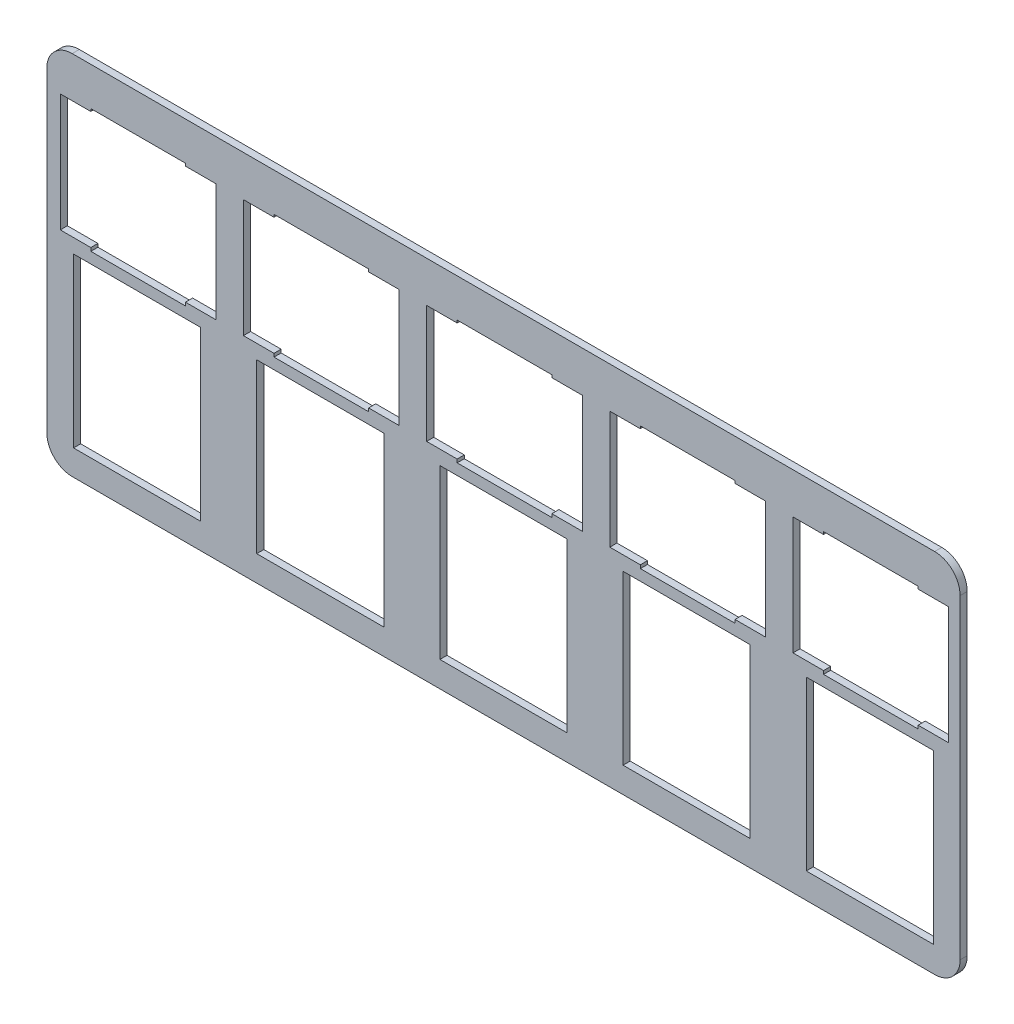
SolidWorks part; units mm, degrees
ref_plane "Ebene vorne" through (0, 0, 0) normal (0, 0, 1) x (1, 0, 0)
ref_plane "Ebene oben" through (0, 0, 0) normal (0, 1, 0) x (1, 0, 0)
ref_plane "Ebene rechts" through (0, 0, 0) normal (1, 0, 0) x (0, 0, -1)
sketch "Skizze1" plane through (0, 0, 0) normal (0, 0, 1) x (1, 0, 0)
  line L1 (-89.75, -36) -> (89.75, -36)
  line L2 (-89.75, -36) -> (-89.75, 36)
  line L3 (-89.75, 36) -> (89.75, 36)
  line L4 (89.75, -36) -> (89.75, 36)
  line L5 (-89.75, -36) -> (89.75, 36) construction
  line L6 (-89.75, 36) -> (89.75, -36) construction
  point P0 (0, 0)
  dimension "D1" = 179.5
  dimension "D2" = 72
extrude "Aufsatz-Linear austragen1" add sketch "Skizze1" along normal blind 1.4
fillet "Verrundung1" radius 5 4 edges at (-89.75, 36, 0.7) (-89.75, -36, 0.7) (89.75, -36, 0.7) (89.75, 36, 0.7)
sketch "Skizze2" plane through (0, 0, 1.4) normal (0, 0, 1) x (1, 0, 0)
  line L0 (63.205, 4.818) -> (81.205, 4.818) construction
  line L1 (59.5127, 27.0001) -> (59.5127, -27.0001) construction
  line L2 (84.4873, -27.0001) -> (84.4873, 27.0001) construction
  line L3 (80.5, 30.9874) -> (63.5, 30.9874) construction
  line L4 (63.205, 4.818) -> (81.205, 4.818) construction
  line L5 (59.5127, 27.0001) -> (59.5127, -27.0001) construction
  line L6 (84.4873, -27.0001) -> (84.4873, 27.0001) construction
  line L7 (80.5, 30.9874) -> (63.5, 30.9874) construction
  line L8 (81.205, 27.818) -> (63.205, 27.818) construction
  line L9 (81.205, 27.818) -> (63.205, 27.818) construction
  line L10 (63.5, -30.9874) -> (80.5, -30.9874) construction
  line L11 (63.5, -30.9874) -> (80.5, -30.9874) construction
  line L13 (84.4873, -30.9874) -> (59.5127, -30.9874)
  line L14 (84.4873, -30.9874) -> (84.4873, 2.0126)
  line L15 (84.4873, 2.0126) -> (59.5127, 2.0126)
  line L16 (59.5127, -30.9874) -> (59.5127, 2.0126)
  dimension "D1" = 33
extrude "Schnitt-Linear austragen1" cut sketch "Skizze2" against normal through all
sketch "Skizze3" plane through (0, 0, 1.4) normal (0, 0, 1) x (1, 0, 0)
  line L0 (63.205, 4.818) -> (81.205, 4.818) construction
  line L1 (62.905, 28.468) -> (81.505, 28.468)
  line L2 (62.905, 28.468) -> (62.905, 27.968)
  line L3 (62.905, 4.168) -> (81.505, 4.168)
  line L4 (81.505, 28.468) -> (81.505, 27.968)
  line L5 (81.205, 27.818) -> (63.205, 27.818) construction
  line L6 (81.205, 26.848) -> (81.205, 27.818) construction
  line L7 (62.905, 4.818) -> (62.905, 4.168)
  line L8 (62.905, 27.968) -> (56.905, 27.968)
  line L10 (62.905, 4.818) -> (56.905, 4.818)
  line L11 (56.905, 27.968) -> (56.905, 4.818)
  line L12 (81.505, 27.968) -> (87.505, 27.968)
  line L14 (81.505, 4.818) -> (87.505, 4.818)
  line L15 (87.505, 27.968) -> (87.505, 4.818)
  line L16 (81.505, 4.818) -> (81.505, 4.168)
  dimension "D1" = 0.65
  dimension "D2" = 0.65
  dimension "D3" = 0.3
  dimension "D4" = 0.3
  dimension "D5" = 0.5
  dimension "D6" = 0.65
  dimension "D7" = 6
extrude "Schnitt-Linear austragen2" cut sketch "Skizze3" against normal through all
pattern_linear "Lineares Muster1" count 5 spacing 36 along (-1, 0, 0) of "Schnitt-Linear austragen1", "Schnitt-Linear austragen2"
